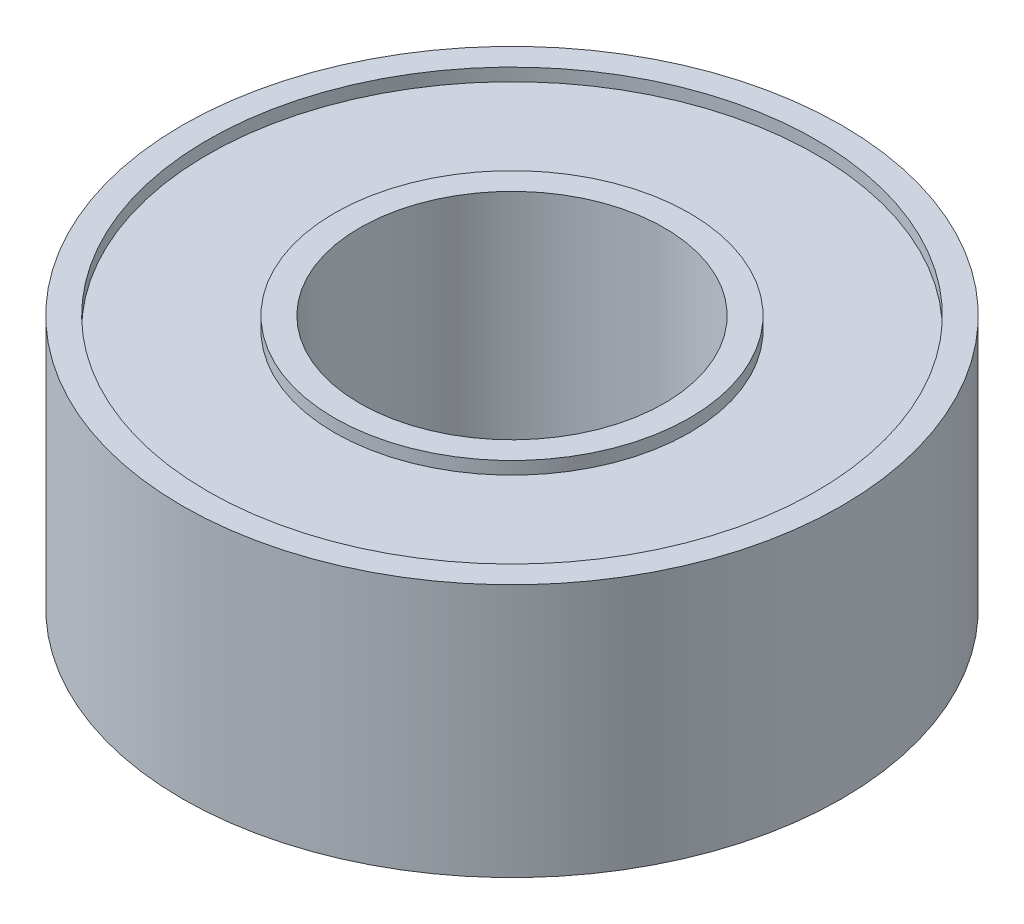
SolidWorks part; units mm, degrees
ref_plane "Front Plane" through (0, 0, 0) normal (0, 0, 1) x (1, 0, 0)
ref_plane "Top Plane" through (0, 0, 0) normal (0, 1, 0) x (1, 0, 0)
ref_plane "Right Plane" through (0, 0, 0) normal (1, 0, 0) x (0, 0, -1)
sketch "Sketch1" plane through (0, 0, 0) normal (0, 1, 0) x (1, 0, 0)
  circle A0 centre (0, 0) radius 3
  circle A1 centre (0, 0) radius 6.5
  dimension "D1" = 6
  dimension "D2" = 13
extrude "Boss-Extrude1" add sketch "Sketch1" along normal blind 5
ref_axis "Axis1" through (0, 5, 0) along (0, -1, 0)
sketch "Sketch2" plane through (0, 0, 0) normal (0, 0, 1) x (1, 0, 0)
  line L0 (6.5, 5) -> (-6.5, 5) construction
  line L1 (-6, 5) -> (-3.5, 5)
  line L2 (-6, 5) -> (-6, 4.75)
  line L3 (-6, 4.75) -> (-3.5, 4.75)
  line L4 (-3.5, 5) -> (-3.5, 4.75)
  line L5 (-6.5, 0) -> (6.5, 0) construction
  line L6 (-6, 0) -> (-3.5, 0)
  line L7 (-6, 0) -> (-6, 0.25)
  line L8 (-6, 0.25) -> (-3.5, 0.25)
  line L9 (-3.5, 0) -> (-3.5, 0.25)
  line L10 (-6.5, 5) -> (-6.5, 0) construction
  line L12 (-3, 5) -> (-3, 0) construction
  dimension "D1" = 0.25
  dimension "D2" = 0.5
  dimension "D3" = 0.5
revolve "Cut-Revolve1" cut sketch "Sketch2" angle 360 about axis through (0, 5, 0) along (0, -1, 0)
